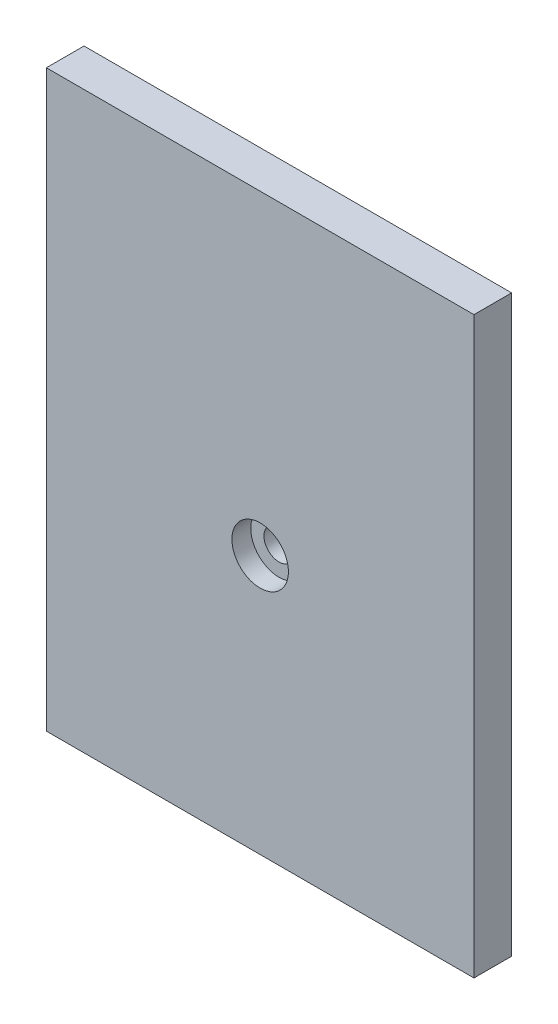
SolidWorks part; units mm, degrees
ref_plane "前视基准面" through (0, 0, 0) normal (0, 0, 1) x (1, 0, 0)
ref_plane "上视基准面" through (0, 0, 0) normal (0, 1, 0) x (1, 0, 0)
ref_plane "右视基准面" through (0, 0, 0) normal (1, 0, 0) x (0, 0, -1)
sketch "草图1" plane through (0, 0, 0) normal (0, 0, 1) x (1, 0, 0)
  line L1 (-72.441, 43.6117) -> (-27.041, 43.6117)
  line L2 (-72.441, 43.6117) -> (-72.441, -17.3883)
  line L3 (-72.441, -17.3883) -> (-27.041, -17.3883)
  line L4 (-27.041, 43.6117) -> (-27.041, -17.3883)
  dimension "D1" = 61
  dimension "D2" = 45.4
extrude "凸台-拉伸1" add sketch "草图1" along normal blind 4
sketch "草图2" plane through (0, 0, 0) normal (0, 0, -1) x (-1, 0, 0)
  line L0 (43.491, 0.6117) -> (43.491, -17.3883)
  line L1 (43.491, 0.6117) -> (55.991, 0.6117)
  line L2 (43.491, -17.3883) -> (55.991, -17.3883)
  line L3 (55.991, 0.6117) -> (55.991, -17.3883)
  line L4 (43.491, 0.6117) -> (55.991, -17.3883) construction
  line L5 (43.491, -17.3883) -> (55.991, 0.6117) construction
  line L6 (72.441, -17.3883) -> (27.041, -17.3883) construction
  point P1 (49.741, -8.3883)
  dimension "D1" = 18
  dimension "D2" = 12.5
  dimension "D3" = 0
extrude "切除-拉伸1" cut sketch "草图2" against normal blind 3.2
sketch "草图3" plane through (0, 0, 0) normal (0, 0, -1) x (-1, 0, 0)
  line L0 (43.491, -17.3883) -> (27.041, -17.3883) construction
  line L1 (49.741, 43.6117) -> (49.741, -17.3883) construction
  line L2 (27.041, 43.6117) -> (72.441, 43.6117) construction
  line L3 (43.491, -17.3883) -> (55.991, -17.3883) construction
  line L4 (72.441, -17.3883) -> (55.991, -17.3883) construction
  line L7 (60.691, -6.8883) -> (66.191, -6.8883)
  line L8 (60.691, -6.8883) -> (60.691, -9.3883)
  line L9 (60.691, -9.3883) -> (66.191, -9.3883)
  line L10 (66.191, -6.8883) -> (66.191, -9.3883)
  line L11 (72.441, 43.6117) -> (72.441, -17.3883) construction
  circle A0 centre (39.741, 0.1117) radius 3.05
  circle A1 centre (39.741, 20.1117) radius 3.05
  circle A2 centre (59.741, 0.1117) radius 3.05
  circle A3 centre (59.741, 20.1117) radius 3.05
  dimension "D1" = 6.1
  dimension "D2" = 17.5
  dimension "D3" = 10
  dimension "D4" = 6.1
  dimension "D5" = 20
  dimension "D6" = 5.5
  dimension "D7" = 2.5
  dimension "D8" = 8
  dimension "D9" = 6.25
sketch "草图4" plane through (0, 0, 4) normal (0, 0, 1) x (1, 0, 0)
  line L0 (-27.041, 43.6117) -> (-72.441, 43.6117) construction
  line L1 (-72.441, 43.6117) -> (-72.441, -17.3883) construction
  circle A0 centre (-49.741, 10.1117) radius 1.6
  dimension "D1" = 3.2
  dimension "D2" = 33.5
  dimension "D3" = 22.7
extrude "切除-拉伸2" cut sketch "草图4" against normal blind 10
sketch "草图5" plane through (0, 0, 4) normal (0, 0, 1) x (1, 0, 0)
  circle A0 centre (-49.741, 10.1117) radius 3
  dimension "D1" = 6
extrude "切除-拉伸3" cut sketch "草图5" against normal blind 2
extrude "凸台-拉伸2" add sketch "草图3" along normal blind 1.5 contours A2 | A3 | A0 | A1 | L7 L10 L9 L8
